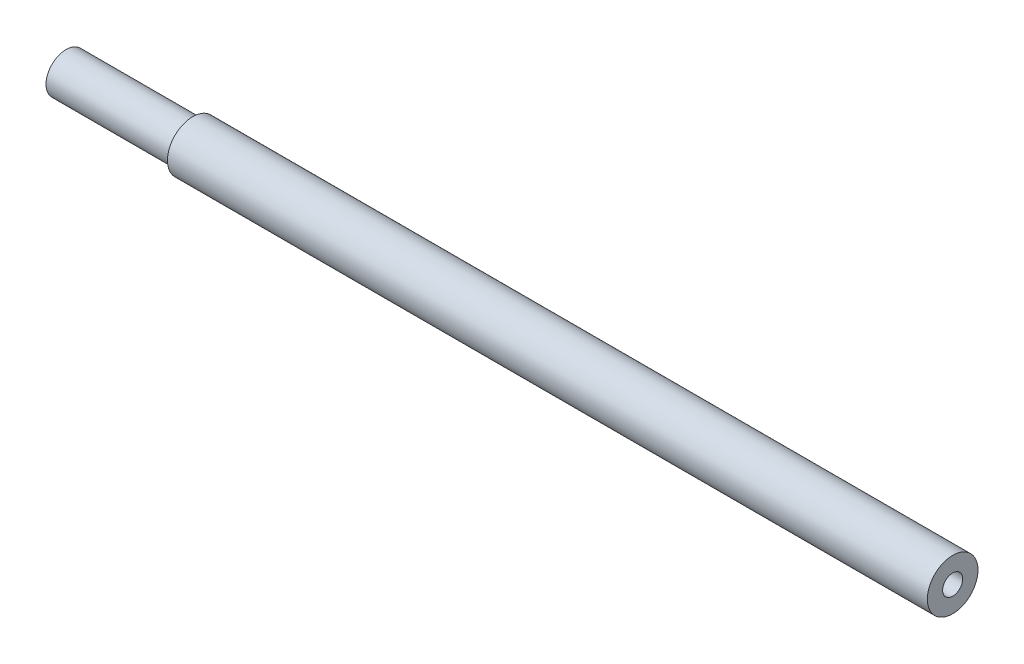
SolidWorks part; units mm, degrees
material "Brass"
ref_plane "Front Plane" through (0, 0, 0) normal (0, 0, 1) x (1, 0, 0)
ref_plane "Top Plane" through (0, 0, 0) normal (0, 1, 0) x (1, 0, 0)
ref_plane "Right Plane" through (0, 0, 0) normal (1, 0, 0) x (0, 0, -1)
sketch "Sketch1" plane through (0, 0, 0) normal (1, 0, 0) x (0, 0, -1)
  circle A0 centre (0, 0) radius 2
  dimension "D1" = 4
extrude "Boss-Extrude1" add sketch "Sketch1" along normal mid plane 60
sketch "Sketch2" plane through (30, 0, 0) normal (1, 0, 0) x (0, 0, -1)
  circle A0 centre (0, 0) radius 0.795
  dimension "D1" = 1.59
extrude "Cut-Extrude1" cut sketch "Sketch2" against normal blind 7
sketch "Sketch3" plane through (-30, 0, 0) normal (-1, 0, 0) x (0, 0, 1)
  circle A0 centre (0, 0) radius 1.5875
  dimension "D1" = 3.175
extrude "Boss-Extrude2" add sketch "Sketch3" along normal blind 10
